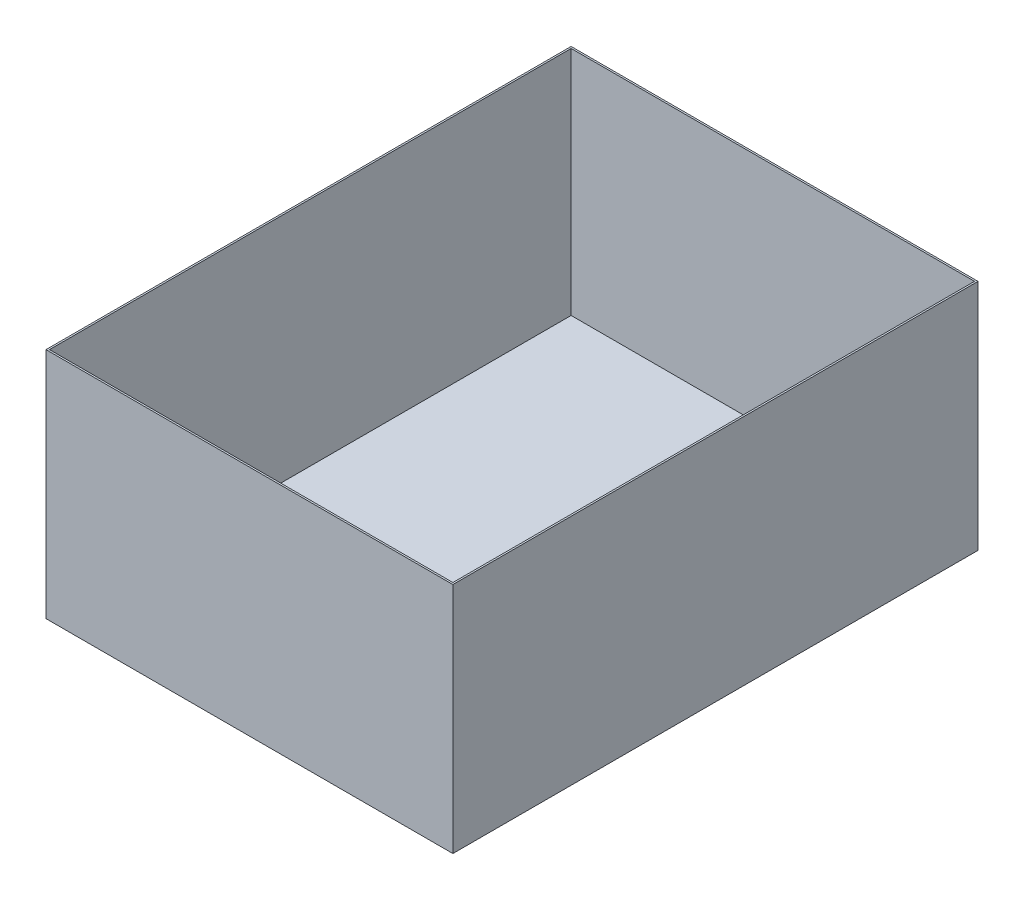
SolidWorks part; units mm, degrees
ref_plane "Front Plane" through (0, 0, 0) normal (0, 0, 1) x (1, 0, 0)
ref_plane "Top Plane" through (0, 0, 0) normal (0, 1, 0) x (1, 0, 0)
ref_plane "Right Plane" through (0, 0, 0) normal (1, 0, 0) x (0, 0, -1)
sketch "Sketch1" plane through (0, 0, 0) normal (0, 1, 0) x (1, 0, 0)
  line L1 (-58.5, 75.5) -> (58.5, 75.5)
  line L2 (-58.5, 75.5) -> (-58.5, -75.5)
  line L3 (-58.5, -75.5) -> (58.5, -75.5)
  line L4 (58.5, 75.5) -> (58.5, -75.5)
  line L5 (-58.5, 75.5) -> (58.5, -75.5) construction
  line L6 (-58.5, -75.5) -> (58.5, 75.5) construction
  point P0 (0, 0)
  dimension "D1" = 151
  dimension "D2" = 117
extrude "Boss-Extrude1" add sketch "Sketch1" along normal mid plane 67
shell "Shell1" thickness 0.5
